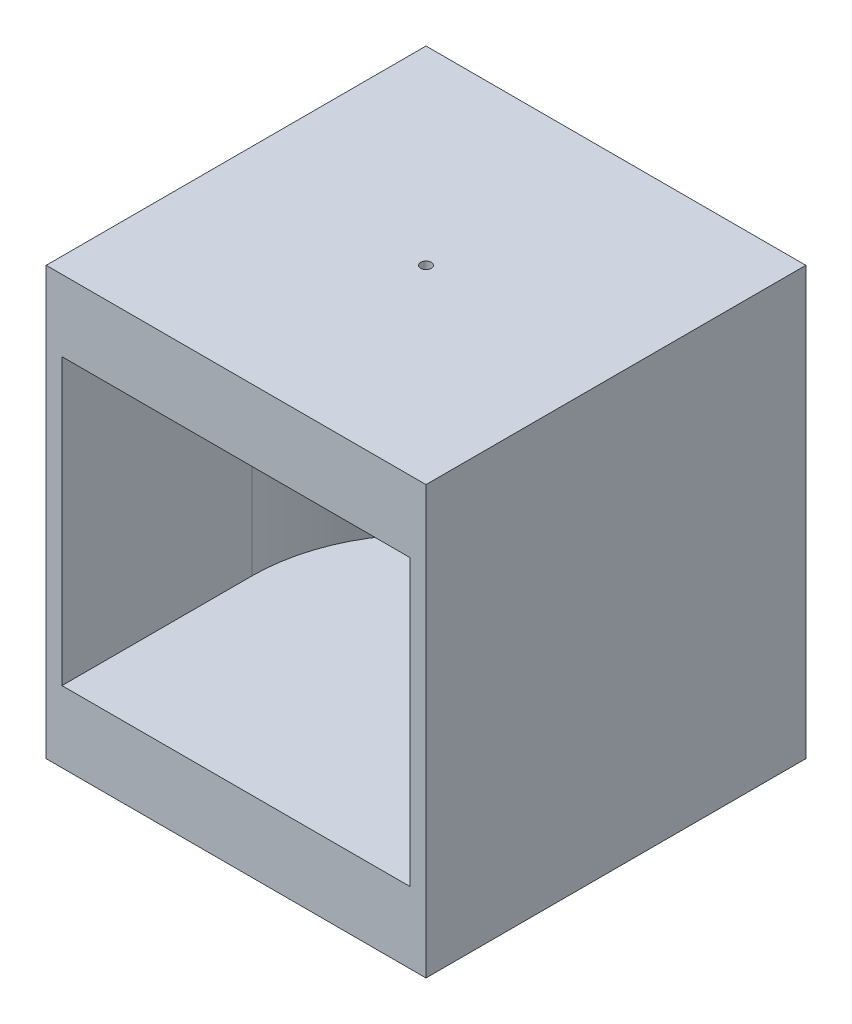
SolidWorks part; units mm, degrees
ref_plane "前视基准面" through (0, 0, 0) normal (0, 0, 1) x (1, 0, 0)
ref_plane "上视基准面" through (0, 0, 0) normal (0, 1, 0) x (1, 0, 0)
ref_plane "右视基准面" through (0, 0, 0) normal (1, 0, 0) x (0, 0, -1)
other "Configuration Table"
sketch "草图2" plane through (0, 0, 0) normal (0, 1, 0) x (1, 0, 0)
  line L1 (-360, -360) -> (360, -360)
  line L2 (-360, -360) -> (-360, 360)
  line L3 (-360, 360) -> (360, 360)
  line L4 (360, -360) -> (360, 360)
  line L5 (-360, -360) -> (360, 360) construction
  line L6 (-360, 360) -> (360, -360) construction
  point P0 (0, 0)
  dimension "D1" = 720
  dimension "D2" = 720
extrude "凸台-拉伸2" add sketch "草图2" along normal mid plane 810
sketch "草图1" plane through (0, 0, 0) normal (0, 1, 0) x (1, 0, 0)
  line L0 (330, 0) -> (330, -360)
  line L7 (-330, 0) -> (-330, -360)
  line L9 (-330, -360) -> (330, -360)
  arc A0 (330, 0) -> (-330, 0) centre (0, 0) ccw
  dimension "D1" = 660
  dimension "D2" = 360
extrude "切除-拉伸1" cut sketch "草图1" against normal mid plane 540
sketch "草图3" plane through (0, 0, 0) normal (0, 1, 0) x (1, 0, 0)
  circle A0 centre (0, 0) radius 10
  dimension "D1" = 20
extrude "切除-拉伸2" cut sketch "草图3" against normal through all both and the other way through all
